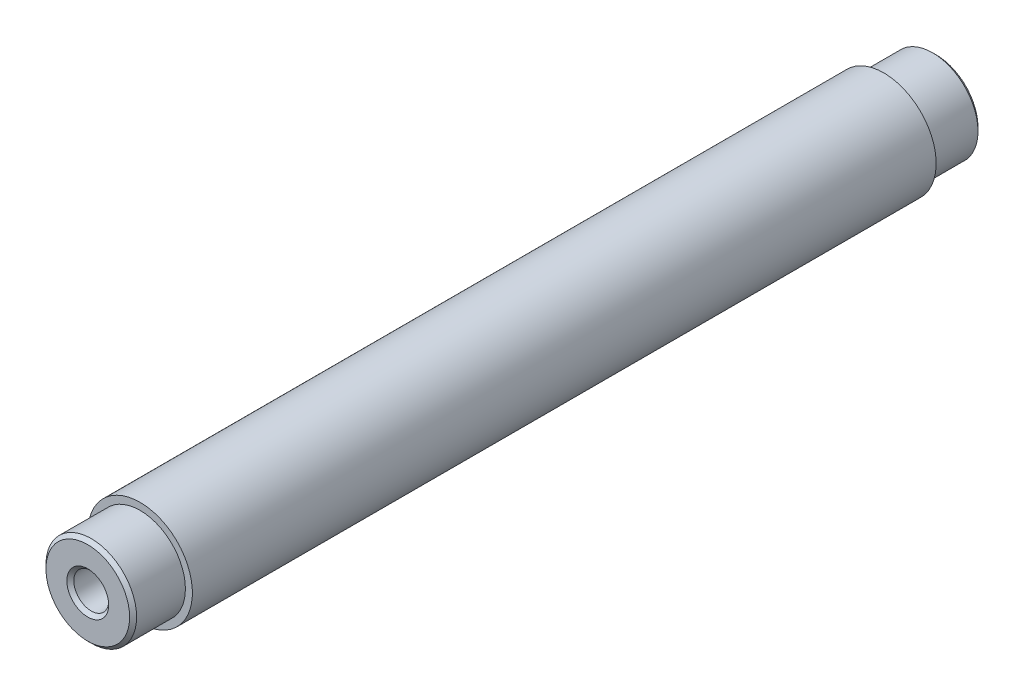
SolidWorks part; units mm, degrees
material "ASTM A36 Aço"
ref_plane "Plano frontal" through (0, 0, 0) normal (0, 0, 1) x (1, 0, 0)
ref_plane "Plano superior" through (0, 0, 0) normal (0, 1, 0) x (1, 0, 0)
ref_plane "Plano direito" through (0, 0, 0) normal (1, 0, 0) x (0, 0, -1)
sketch "Esboço1" plane through (0, 0, 0) normal (0, 0, 1) x (1, 0, 0)
  circle A0 centre (0, 0) radius 7.5
  dimension "D1" = 15
extrude "Ressalto-extrusão1" add sketch "Esboço1" along normal mid plane 121.65
sketch "Esboço2" plane through (0, 0, -60.825) normal (0, 0, -1) x (-1, 0, 0)
  circle A2 centre (0, 0) radius 6.5
  circle A3 centre (0, 0) radius 7.5
  circle A4 centre (0, 0) radius 7.5 construction
  dimension "D1" = 13
extrude "Corte-extrusão1" cut sketch "Esboço2" against normal blind 7.5
hole_wizard "Furo roscado de M6x1.01" positions "Esboço6" profile "Esboço7" tap size "M6x1.0" standard "Ansi Metric"
sketch "Esboço6" plane through (0, 0, -60.825) normal (0, 0, -1) x (-1, 0, 0)
  point P0 (0, 0)
sketch "Esboço7" plane through (0, 0, -60.825) normal (1, 0, 0) x (0, 1, 0)
  line L0 (0, 0) -> (0, 17)
  line L1 (0, 17) -> (2.5, 15.4978)
  line L2 (2.5, 15.4978) -> (2.5, 0)
  line L5 (2.5, 0) -> (0, 0)
  line L10 (0, 17) -> (-2.5, 15.4978) construction
  line L11 (0, -6.35) -> (0, 107.95) construction
  dimension "Tap Drill Dia." = 5
  dimension "Tap Drill Depth" = 17
  dimension "Drill Angle" = 118
cosmetic thread "Rosca de furo1" parameters "D1"=12, "D2"=6
mirror "Espelhar1" about plane through (0, 0, 0) normal (0, 0, 1) of "Furo roscado de M6x1.01", "Corte-extrusão1"
cosmetic thread "Rosca de furo2" parameters "D1"=12, "D2"=6
chamfer "Chanfro1" distance 0.5 angle 45 4 edges at (-6.5, 0, -60.825) (-6.5, 0, 60.825) (2.5, 0, 60.825) (-2.5, 0, -60.825)
